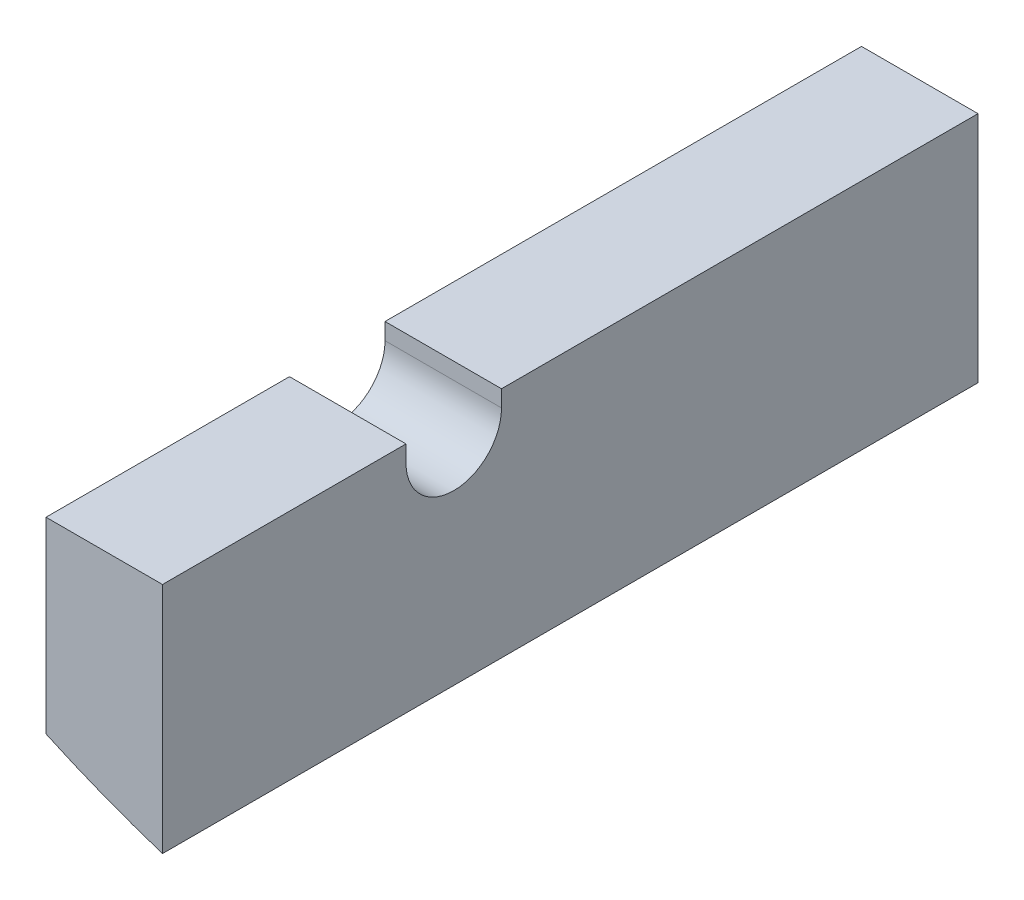
SolidWorks part; units mm, degrees
ref_plane "Plan de face" through (0, 0, 0) normal (0, 0, 1) x (1, 0, 0)
ref_plane "Plan de dessus" through (0, 0, 0) normal (0, 1, 0) x (1, 0, 0)
ref_plane "Plan de droite" through (0, 0, 0) normal (1, 0, 0) x (0, 0, -1)
sketch "Esquisse1" plane through (0, 0, 0) normal (0, 0, 1) x (1, 0, 0)
  line L0 (-19, -41.3431) -> (-19, -32.2926)
  line L1 (-19, -32.2926) -> (-14, -32.2926)
  line L2 (-14, -32.2926) -> (-14, -43.2926)
  arc A0 (-19, -41.3431) -> (-14, -43.2926) centre (0, 0) ccw
  dimension "D1" = 11
extrude "Boss.-Extru.1" add sketch "Esquisse1" along normal blind 35
sketch "Esquisse2" plane through (-19, 0, 0) normal (-1, 0, 0) x (0, 0, 1)
  line L0 (22.5, -27.9926) -> (22.5, -46.9231) construction
  line L1 (0, -32.2926) -> (0, -41.3431) construction
  line L2 (35, -32.2926) -> (0, -32.2926) construction
  line L3 (24.55, -34.0026) -> (24.55, -32.2926)
  line L4 (24.55, -32.2926) -> (22.5, -31.9526)
  line L5 (20.45, -34.0026) -> (20.45, -32.2926)
  line L6 (20.45, -32.2926) -> (22.5, -31.9526)
  arc A0 (20.45, -34.0026) -> (24.55, -34.0026) centre (22.5, -34.0026) ccw
  dimension "D2" = 1.71
  dimension "D3" = 4.1
  dimension "D1" = 22.5
extrude "Enlèv. mat.-Extru.2" cut sketch "Esquisse2" against normal through all
sketch "Esquisse4" plane through (-19, 0, 0) normal (-1, 0, 0) x (0, 0, 1)
  line L0 (35, -32.2926) -> (35, -41.3431) construction
  line L1 (0, -32.2926) -> (35, -32.2926)
  line L2 (0, -32.2926) -> (0, -33.289)
  line L3 (0, -33.289) -> (35, -33.289)
  line L4 (35, -32.2926) -> (35, -33.289)
extrude "Enlèv. mat.-Extru.3" cut sketch "Esquisse4" against normal blind 35
